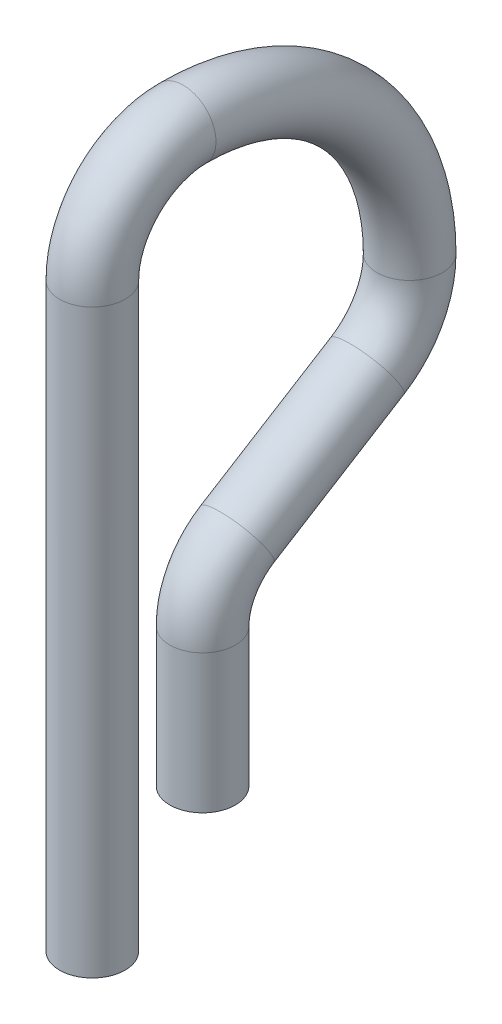
SolidWorks part; units mm, degrees
ref_plane "Front Plane" through (0, 0, 0) normal (1, 0, 0) x (0, 1, 0)
ref_plane "Top Plane" through (0, 0, 0) normal (0, 0, 1) x (0, 1, 0)
ref_plane "Right Plane" through (0, 0, 0) normal (0, 1, 0) x (-1, 0, 0)
sketch "Sketch1" plane through (0, 0, 0) normal (1, 0, 0) x (0, 1, 0)
  line L0 (0, 0) -> (99.06, 0)
  line L1 (62.992, -46.8902) -> (49.2539, -24.7229)
  line L2 (38.608, -18.796) -> (14.986, -18.796)
  arc A0 (99.06, 0) -> (114.554, -15.494) centre (99.06, -15.494) cw
  arc A1 (49.2539, -24.7229) -> (38.608, -18.796) centre (38.608, -31.3206) ccw
  arc A2 (114.554, -15.494) -> (75.946, -54.102) centre (75.946, -15.494) cw
  arc A3 (75.946, -54.102) -> (62.992, -46.8902) centre (75.946, -38.862) cw
  point P8 (26.797, -18.796)
  point P12 (0, 0)
  point P13 (90.1281, -51.4028)
  point P14 (46.4564, -18.796)
  point P15 (83.0211, -53.4482)
  point P18 (0, 0)
  point P19 (61.0878, -36.3546)
  point P20 (0, 0)
  point P21 (113.3544, -9.5162)
  point P22 (0, 0)
  point P23 (0, 0)
  dimension "D2" = 15.494
  dimension "D4" = 38.608
  dimension "D1" = 99.06
  dimension "D3" = 18.796
  dimension "D5" = 36.068
  dimension "D6" = 60.452
  dimension "D7" = 84.074
  dimension "D8" = 23.114
  dimension "D9" = 23.368
sweep "Sweep1" add path "Sketch1" circular profile diameter 11.176 parameters "D3"=11.176
